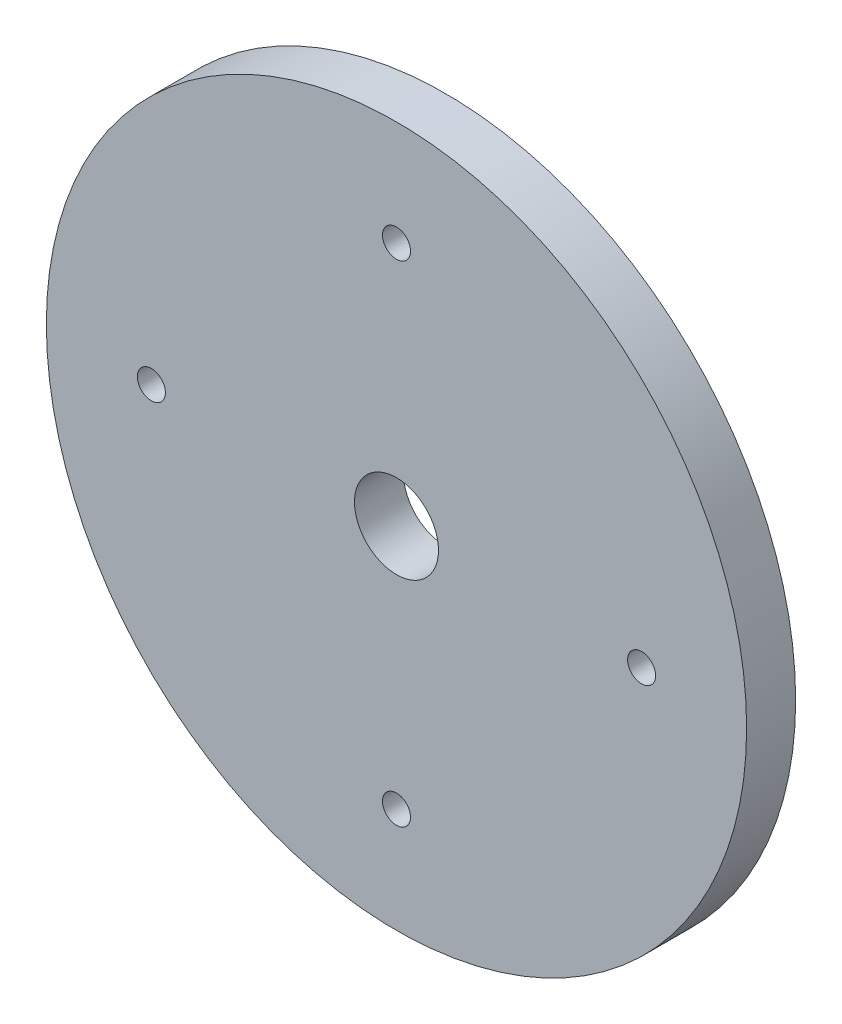
SolidWorks part; units mm, degrees
ref_plane "Front Plane" through (0, 0, 0) normal (0, 0, 1) x (1, 0, 0)
ref_plane "Top Plane" through (0, 0, 0) normal (0, 1, 0) x (1, 0, 0)
ref_plane "Right Plane" through (0, 0, 0) normal (1, 0, 0) x (0, 0, -1)
sketch "Sketch1" plane through (0, 0, 0) normal (0, 0, 1) x (1, 0, 0)
  circle A0 centre (0, 0) radius 6
  circle A1 centre (0, 0) radius 50
  dimension "D1" = 12
  dimension "D2" = 100
extrude "Boss-Extrude1" add sketch "Sketch1" along normal blind 7
sketch "Sketch2" plane through (0, 0, 7) normal (0, 0, 1) x (1, 0, 0)
  line L0 (0, 18.0512) -> (0, 79.0405) construction
  line L1 (-2.5198, 0) -> (97.6434, 0) construction
  line L2 (-35, 0) -> (0, 0) construction
  line L3 (0, 0) -> (35, 0) construction
  line L4 (0, 35) -> (0, 0) construction
  line L5 (0, -35) -> (0, 0) construction
  circle A0 centre (0, 35) radius 2
  circle A1 centre (0, -35) radius 2
  circle A2 centre (-35, 0) radius 2
  circle A3 centre (35, 0) radius 2
  point P4 (0, 0)
  dimension "D1" = 4
  dimension "D2" = 35
extrude "Cut-Extrude1" cut sketch "Sketch2" against normal through all
